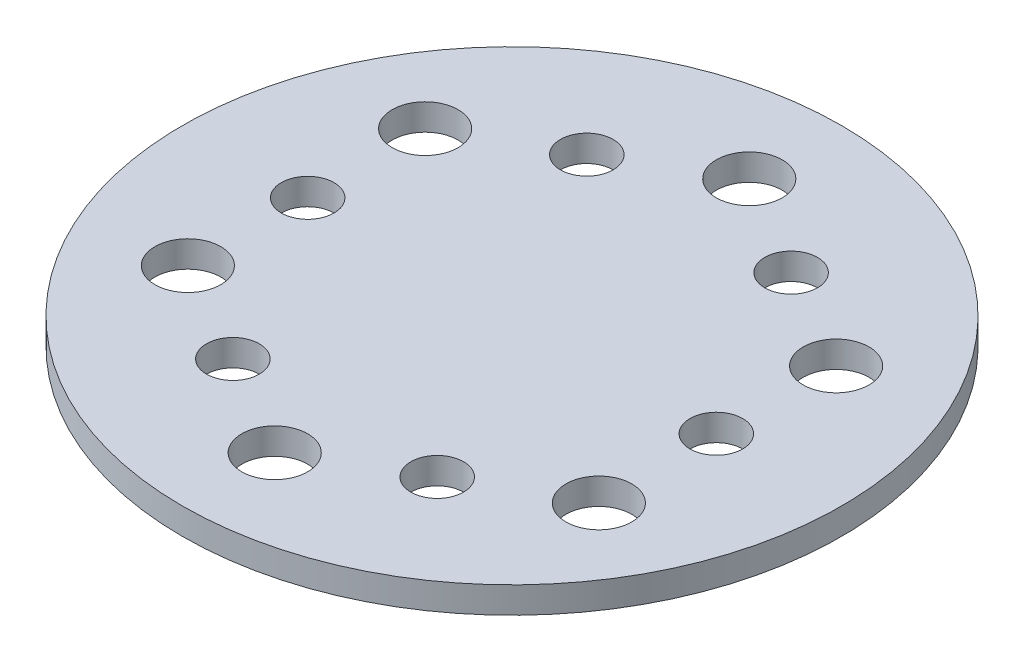
SolidWorks part; units mm, degrees
ref_plane "Спереди" through (0, 0, 0) normal (0, 0, 1) x (1, 0, 0)
ref_plane "Сверху" through (0, 0, 0) normal (0, 1, 0) x (1, 0, 0)
ref_plane "Справа" through (0, 0, 0) normal (1, 0, 0) x (0, 0, -1)
other "Configuration Table"
sketch "Эскиз1" plane through (0, 0, 0) normal (0, 1, 0) x (1, 0, 0)
  circle A0 centre (0, 0) radius 25
  dimension "D1" = 50
extrude "Бобышка-Вытянуть1" add sketch "Эскиз1" along normal blind 2
sketch "Эскиз2" plane through (0, 2, 0) normal (0, 1, 0) x (1, 0, 0)
  line L0 (0, 0) -> (0, 18) construction
  line L1 (0, 0) -> (-15.5, 0) construction
  circle A0 centre (0, 0) radius 18 construction
  circle A1 centre (0, 0) radius 15.5 construction
  circle A2 centre (0, 18) radius 2.5
  circle A3 centre (0, 0) radius 18 construction
  circle A4 centre (15.5885, 9) radius 2.5
  circle A6 centre (15.5885, -9) radius 2.5
  circle A8 centre (0, -18) radius 2.5
  circle A10 centre (-15.5885, -9) radius 2.5
  circle A12 centre (-15.5885, 9) radius 2.5
  circle A13 centre (-15.5, 0) radius 2
  circle A15 centre (-7.75, 13.4234) radius 2
  circle A17 centre (7.75, 13.4234) radius 2
  circle A19 centre (15.5, 0) radius 2
  circle A21 centre (7.75, -13.4234) radius 2
  circle A23 centre (-7.75, -13.4234) radius 2
  circle A24 centre (0, 0) radius 15.5 [skipped]
  circle A25 centre (0, 0) radius 15.5 [skipped]
  circle A26 centre (0, 0) radius 15.5 [skipped]
  circle A27 centre (0, 0) radius 15.5 [skipped]
  circle A28 centre (0, 0) radius 15.5 [skipped]
  circle A29 centre (0, 0) radius 18 [skipped]
  circle A30 centre (0, 0) radius 18 [skipped]
  circle A31 centre (0, 0) radius 18 [skipped]
  circle A32 centre (0, 0) radius 18 [skipped]
  dimension "D1" = 36
  dimension "D2" = 31
  dimension "D3" = 5
  dimension "D5" = 4
  dimension "D4" = 6
  dimension "D6" = 6
extrude "Вырез-Вытянуть1" cut sketch "Эскиз2" against normal blind 2 contours A13 | A6 | A4 | A2 | A10 | A8 | A15 | A12 | A23 | A21 | A19 | A17
